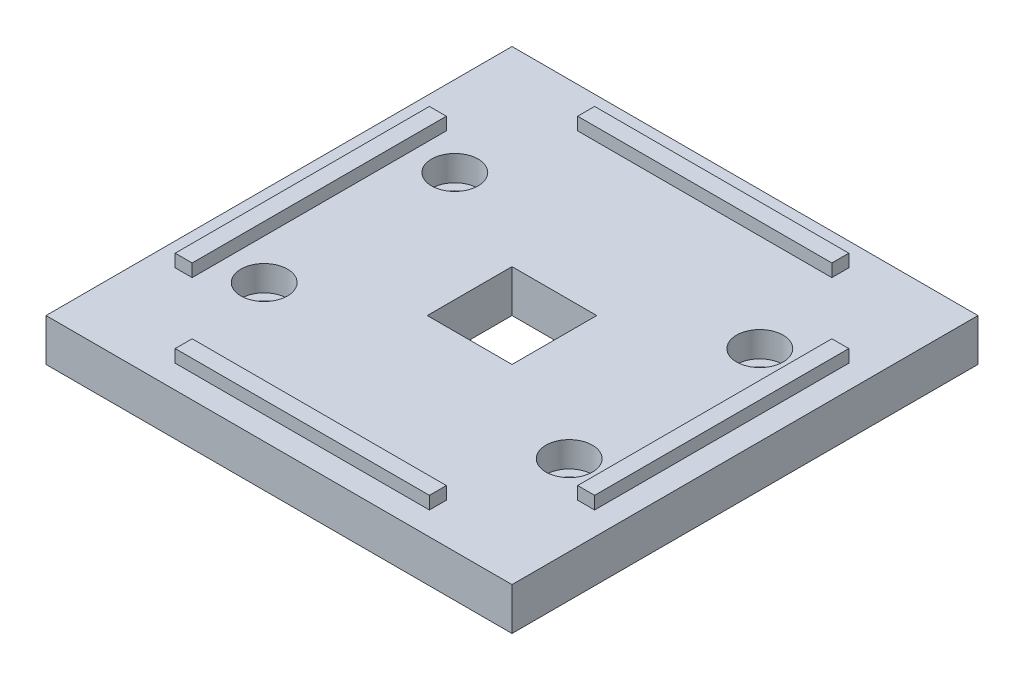
SolidWorks part; units mm, degrees
ref_plane "Alzado" through (0, 0, 0) normal (0, 0, 1) x (1, 0, 0)
ref_plane "Planta" through (0, 0, 0) normal (0, 1, 0) x (1, 0, 0)
ref_plane "Vista lateral" through (0, 0, 0) normal (1, 0, 0) x (0, 0, -1)
sketch "Croquis1" plane through (0, 0, 0) normal (0, 1, 0) x (1, 0, 0)
  line L1 (0, 0) -> (55, 0)
  line L2 (0, 0) -> (0, 55)
  line L3 (0, 55) -> (55, 55)
  line L4 (55, 0) -> (55, 55)
  dimension "D1" = 55
extrude "Saliente-Extruir1" add sketch "Croquis1" along normal blind 5
sketch "Croquis2" plane through (0, 5, 0) normal (0, 1, 0) x (1, 0, 0)
  line L0 (27.5, 0) -> (27.5, 55) construction
  line L1 (0, 0) -> (55, 0) construction
  line L2 (55, 55) -> (0, 55) construction
  line L3 (0, 27.5) -> (55, 27.5) construction
  line L4 (0, 55) -> (0, 0) construction
  line L5 (55, 0) -> (55, 55) construction
  line L6 (12.5, 52.25) -> (42.5, 52.25)
  line L7 (4.75, 4.75) -> (50.25, 4.75) construction
  line L8 (4.75, 4.75) -> (4.75, 50.25) construction
  line L9 (4.75, 50.25) -> (50.25, 50.25) construction
  line L10 (50.25, 4.75) -> (50.25, 50.25) construction
  line L11 (2.75, 12.5) -> (4.75, 12.5)
  line L12 (2.75, 12.5) -> (2.75, 42.5)
  line L13 (2.75, 42.5) -> (4.75, 42.5)
  line L14 (4.75, 12.5) -> (4.75, 42.5)
  line L15 (12.5, 52.25) -> (12.5, 50.25)
  line L16 (12.5, 50.25) -> (42.5, 50.25)
  line L17 (42.5, 52.25) -> (42.5, 50.25)
  line L18 (52.25, 42.5) -> (52.25, 12.5)
  line L19 (52.25, 42.5) -> (50.25, 42.5)
  line L20 (50.25, 42.5) -> (50.25, 12.5)
  line L21 (52.25, 12.5) -> (50.25, 12.5)
  line L22 (42.5, 2.75) -> (12.5, 2.75)
  line L23 (42.5, 2.75) -> (42.5, 4.75)
  line L24 (42.5, 4.75) -> (12.5, 4.75)
  line L25 (12.5, 2.75) -> (12.5, 4.75)
  point P16 (27.5, 4.75)
  point P17 (4.75, 27.5)
  point P22 (2.75, 27.5)
  dimension "D1" = 45.5
  dimension "D2" = 30
  dimension "D3" = 2
  dimension "D4" = 4
extrude "Saliente-Extruir2" add sketch "Croquis2" along normal blind 1.5 contours L12 L11 L14 L13 | L22 L25 L24 L23 | L18 L21 L20 L19 | L6 L17 L16 L15
sketch "Croquis3" plane through (0, 5, 0) normal (0, 1, 0) x (1, 0, 0)
  line L0 (27.5, 0) -> (27.5, 55) construction
  line L1 (0, 0) -> (55, 0) construction
  line L2 (55, 55) -> (0, 55) construction
  line L3 (9.5, 16.25) -> (9.5, 38.75) construction
  line L4 (9.5, 27.5) -> (27.5, 27.5) construction
  circle A0 centre (9.5, 38.75) radius 1.6
  circle A1 centre (9.5, 16.25) radius 1.6
  circle A2 centre (45.5, 38.75) radius 1.6
  circle A3 centre (45.5, 16.25) radius 1.6
  dimension "D1" = 18
  dimension "D3" = 3.2
  dimension "D2" = 22.5
extrude "Cortar-Extruir1" cut sketch "Croquis3" against normal blind 5
sketch "Croquis6" plane through (0, 5, 0) normal (0, 1, 0) x (1, 0, 0)
  line L0 (27.5, 32.5) -> (27.5, 55) construction
  line L1 (22.5, 22.5) -> (32.5, 22.5)
  line L2 (22.5, 22.5) -> (22.5, 32.5)
  line L3 (22.5, 32.5) -> (32.5, 32.5)
  line L4 (32.5, 22.5) -> (32.5, 32.5)
  line L5 (55, 55) -> (0, 55) construction
  line L6 (32.5, 27.5) -> (55, 27.5) construction
  line L7 (55, 0) -> (55, 55) construction
  dimension "D1" = 10
extrude "Cortar-Extruir4" cut sketch "Croquis6" against normal blind 10
sketch "Croquis7" plane through (0, 5, 0) normal (0, 1, 0) x (1, 0, 0)
  circle A0 centre (9.5, 38.75) radius 2.75
  circle A1 centre (45.5, 38.75) radius 2.75
  circle A2 centre (45.5, 16.25) radius 2.75
  circle A3 centre (9.5, 16.25) radius 2.75
  dimension "D1" = 5.5
extrude "Cortar-Extruir5" cut sketch "Croquis7" against normal blind 3
